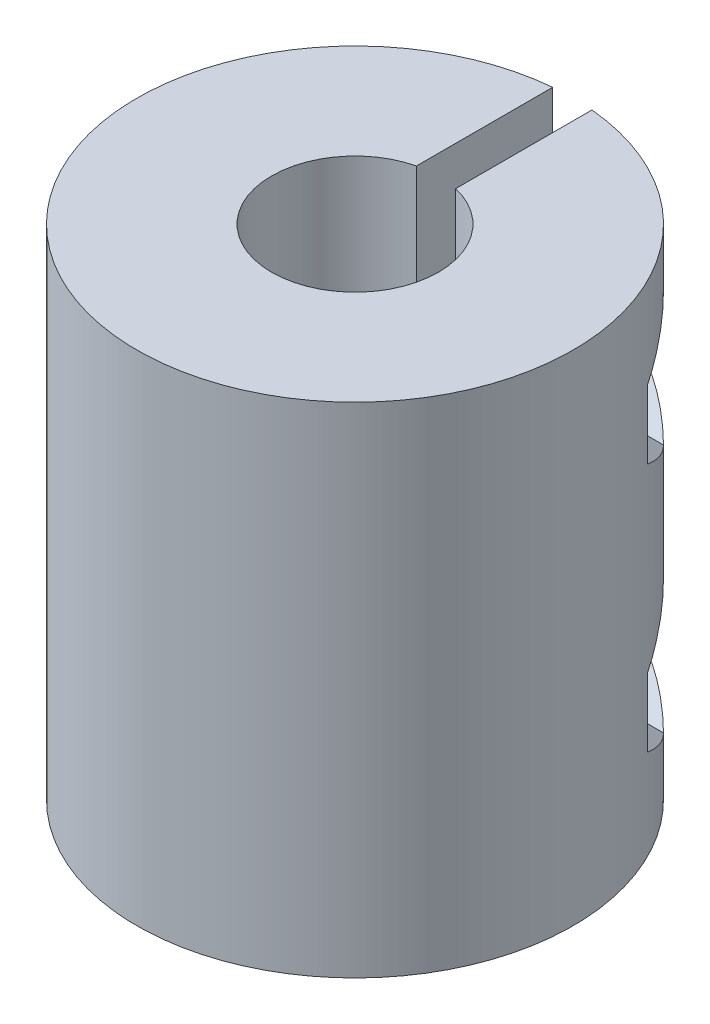
SolidWorks part; units mm, degrees
ref_plane "Front Plane" through (0, 0, 0) normal (0, 0, 1) x (1, 0, 0)
ref_plane "Top Plane" through (0, 0, 0) normal (0, 1, 0) x (1, 0, 0)
ref_plane "Right Plane" through (0, 0, 0) normal (1, 0, 0) x (0, 0, -1)
sketch "Sketch1" plane through (0, 0, 0) normal (0, 1, 0) x (1, 0, 0)
  circle A0 centre (0, 0) radius 11.1125
  dimension "D1" = 22.225
extrude "Boss-Extrude1" add sketch "Sketch1" along normal mid plane 25.4
sketch "Sketch2" plane through (0, 12.7, 0) normal (0, 1, 0) x (1, 0, 0)
  circle A0 centre (0, 0) radius 4.25
  dimension "D1" = 8.5
extrude "Cut-Extrude1" cut sketch "Sketch2" against normal up to surface (12.7 mm away)
sketch "Sketch3" plane through (0, -12.7, 0) normal (0, -1, 0) x (1, 0, 0)
  circle A0 centre (0, 0) radius 4.8895
  dimension "D1" = 9.779
extrude "Cut-Extrude2" cut sketch "Sketch3" against normal up to surface (12.7 mm away)
sketch "Sketch4" plane through (0, 12.7, 0) normal (0, 1, 0) x (1, 0, 0)
  line L0 (-1, 4.1307) -> (-1, 11.0674)
  line L1 (1, 11.0674) -> (1, 4.1307)
  circle A0 centre (0, 0) radius 4.25 construction
  circle A1 centre (0, 0) radius 11.1125
  arc A2 (1, 11.0674) -> (-1, 11.0674) centre (0, 0) ccw
  arc A3 (1, 4.1307) -> (-1, 4.1307) centre (0, 0) ccw
  dimension "D2" = 2
  dimension "D1" = 0
extrude "Cut-Extrude3" cut sketch "Sketch4" against normal up to next
ref_plane "Plane1" through (7, 0, 0) normal (-1, 0, 0) x (0, 0, 1)
sketch "Sketch5" plane through (7, 0, 0) normal (1, 0, 0) x (0, 0, -1)
  line L0 (7.9268, -6.35) -> (7.9268, 6.35) construction
  line L1 (7.9268, 2.8859) -> (10.9268, 4.6179)
  line L2 (10.9268, 4.6179) -> (10.9268, 8.0821)
  line L3 (10.9268, 8.0821) -> (7.9268, 9.8141)
  line L4 (7.9268, 9.8141) -> (4.9268, 8.0821)
  line L5 (4.9268, 8.0821) -> (4.9268, 4.6179)
  line L6 (4.9268, 4.6179) -> (7.9268, 2.8859)
  line L7 (7.9268, -9.8141) -> (10.9268, -8.0821)
  line L8 (10.9268, -8.0821) -> (10.9268, -4.6179)
  line L9 (10.9268, -4.6179) -> (7.9268, -2.8859)
  line L10 (7.9268, -2.8859) -> (4.9268, -4.6179)
  line L11 (4.9268, -4.6179) -> (4.9268, -8.0821)
  line L12 (4.9268, -8.0821) -> (7.9268, -9.8141)
  line L13 (11.0674, -12.7) -> (4.7861, -12.7) construction
  circle A0 centre (7.9268, 6.35) radius 3 construction
  circle A1 centre (7.9268, -6.35) radius 3 construction
  point P9 (7.9268, 0)
  point P21 (7.9268, -12.7)
  dimension "D1" = 6
  dimension "D2" = 6.35
extrude "Cut-Extrude4" cut sketch "Sketch5" against normal blind 4 and the other way up to next
hole_wizard "M3 Clearance Hole1" positions "Sketch6" profile "Sketch7" hole size "M3" standard "ANSI Metric" end condition through all
sketch "Sketch6" plane through (3, 0, 0) normal (1, 0, 0) x (0, 0, -1)
  point P0 (7.9268, 6.35)
  point P3 (7.9268, -6.35)
sketch "Sketch7" plane through (3, 6.35, -7.9268) normal (0, 1, 0) x (0, 0, -1)
  line L0 (0, 0) -> (0, 14.1125)
  line L1 (0, 14.1125) -> (1.7, 14.1125)
  line L2 (1.7, 14.1125) -> (1.7, 0)
  line L5 (1.7, 0) -> (0, 0)
  line L11 (0, -6.35) -> (0, 107.95) construction
  dimension "Thru Hole Dia." = 3.4
  dimension "Thru Hole Depth" = 14.1125
ref_plane "Plane2" through (-3, 0, 0) normal (1, 0, 0) x (0, 0, -1)
sketch "Sketch9" plane through (-3, 0, 0) normal (1, 0, 0) x (0, 0, -1)
  circle A0 centre (7.9268, 6.35) radius 3.5
  circle A1 centre (7.9268, -6.35) radius 3.5
  dimension "D1" = 7
extrude "Cut-Extrude5" cut sketch "Sketch9" against normal up to next
